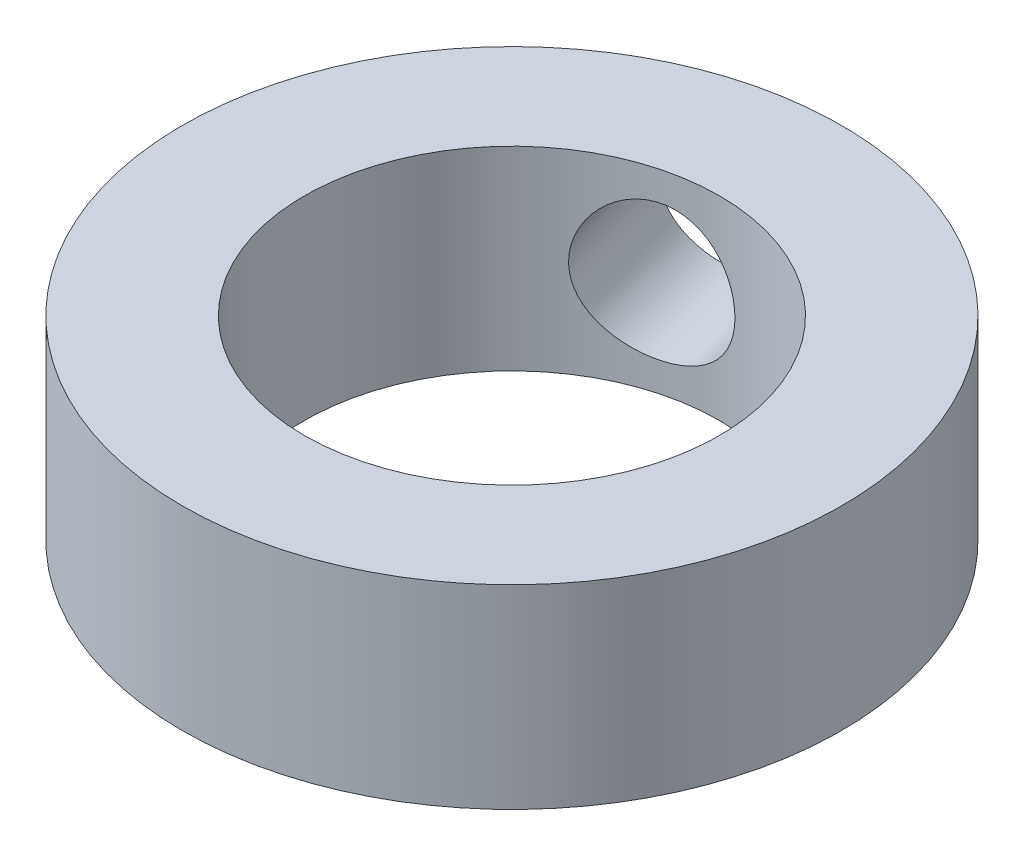
SolidWorks part; units mm, degrees
ref_plane "Front Plane" through (0, 0, 0) normal (0, 0, 1) x (1, 0, 0)
ref_plane "Top Plane" through (0, 0, 0) normal (0, 1, 0) x (1, 0, 0)
ref_plane "Right Plane" through (0, 0, 0) normal (1, 0, 0) x (0, 0, -1)
sketch "Sketch1" plane through (0, 0, 0) normal (0, 1, 0) x (1, 0, 0)
  circle A0 centre (0, 0) radius 25.4
extrude "Boss-Extrude1" add sketch "Sketch1" along normal blind 15
sketch "Sketch2" plane through (0, 15, 0) normal (0, 1, 0) x (1, 0, 0)
  circle A0 centre (0, 0) radius 16
extrude "Cut-Extrude1" cut sketch "Sketch2" against normal blind 15
hole_wizard "Ø10.5 (10.5) Diameter Hole1" positions "3DSketch1" profile "Sketch3" hole size "Ø10.5" standard "Ansi Metric"
sketch3d "3DSketch1"
  line L0 (0, 0, 0) -> (-6.4569, 0, -24.5656)
  line L1 (-6.4569, 0, -24.5656) -> (-6.4569, 7.5, -24.5656)
  circle A0 centre (0, 0, 0) radius 25.4 construction
  point P0 (-6.4569, 7.5, -24.5656)
  point P7 (0, 25.4, 0)
  dimension "D1" = 7.5
sketch "Sketch3" plane through (-6.4569, 7.5, -24.5656) normal (0, 1, 0) x (-0.9671, 0, 0.2542)
  line L0 (0, 0) -> (0, 33.1545)
  line L1 (0, 33.1545) -> (5.25, 30)
  line L2 (5.25, 30) -> (5.25, 0)
  line L5 (5.25, 0) -> (0, 0)
  line L10 (0, 33.1545) -> (-5.25, 30) construction
  line L11 (0, -6.35) -> (0, 107.95) construction
  dimension "Hole Dia." = 10.5
  dimension "Hole Depth" = 30
  dimension "Drill Angle" = 118
